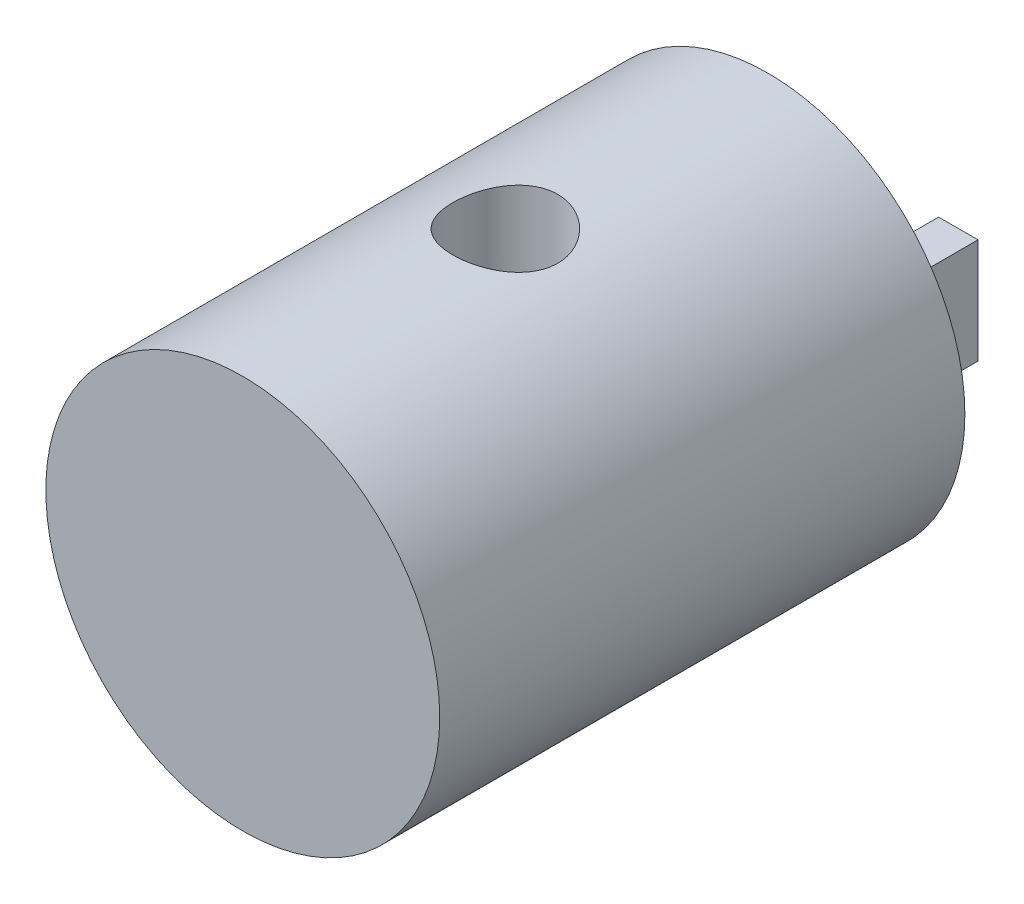
SolidWorks part; units mm, degrees
ref_plane "Alzado" through (0, 0, 0) normal (0, 0, 1) x (1, 0, 0)
ref_plane "Planta" through (0, 0, 0) normal (0, 1, 0) x (1, 0, 0)
ref_plane "Vista lateral" through (0, 0, 0) normal (1, 0, 0) x (0, 0, -1)
sketch "Croquis1" plane through (0, 0, 0) normal (0, 0, 1) x (1, 0, 0)
  circle A0 centre (0, 0) radius 7.5
  dimension "D1" = 15
extrude "Saliente-Extruir1" add sketch "Croquis1" along normal blind 20
sketch "Croquis2" plane through (0, 0, 20) normal (0, 0, 1) x (1, 0, 0)
  line L0 (-2.5, 2) -> (-2.5, -2)
  line L1 (-2.5, -2) -> (2.5, -2)
  line L2 (2.5, -2) -> (2.5, 2)
  line L3 (2.5, 2) -> (-2.5, 2)
  point P2 (0, 2)
  point P5 (2.5, 0)
  dimension "D1" = 5
  dimension "D2" = 4
extrude "Saliente-Extruir2" add sketch "Croquis2" along normal blind 4
sketch "Croquis4" plane through (0, 0, 0) normal (0, 0, -1) x (-1, 0, 0)
  line L0 (-4, 2) -> (-4, -2)
  line L1 (-4, -2) -> (4, -2)
  line L2 (4, -2) -> (4, 2)
  line L3 (4, 2) -> (-4, 2)
  point P5 (4, 0)
  point P8 (0, -2)
  dimension "D1" = 8
  dimension "D2" = 4
extrude "Saliente-Extruir4" add sketch "Croquis4" along normal blind 4
sketch "Croquis6" plane through (0, 2, 0) normal (0, 1, 0) x (1, 0, 0)
  line L0 (-2.5, 4) -> (-2.5, 0)
  line L1 (-2.5, 0) -> (2.5, 0)
  line L2 (2.5, 0) -> (2.5, 4)
  line L3 (2.5, 4) -> (-2.5, 4)
  line L4 (-1.25, -20) -> (-1.25, -24)
  line L5 (-1.25, -24) -> (1.25, -24)
  line L6 (1.25, -24) -> (1.25, -20)
  line L7 (1.25, -20) -> (-1.25, -20)
  line L10 (-4, 4) -> (4, 4) construction
  line L11 (2.5, -24) -> (-2.5, -24) construction
  point P12 (0, 4)
  point P13 (0, 4)
  point P14 (0, -24)
  point P15 (0, -24)
  dimension "D1" = 5
  dimension "D2" = 4
  dimension "D3" = 4
  dimension "D4" = 2.5
extrude "Cortar-Extruir1" cut sketch "Croquis6" against normal up to next
sketch "Croquis7" plane through (-4, 0, 0) normal (-1, 0, 0) x (0, 0, 1)
  line L0 (-4, -2) -> (-4, 2) construction
  line L1 (24, 2) -> (24, -2) construction
  circle A0 centre (-2.5, 0) radius 1
  circle A1 centre (22.5, 0) radius 1
  dimension "D3" = 2
  dimension "D4" = 2
  dimension "D1" = 1.5
  dimension "D2" = 1.5
extrude "Cortar-Extruir2" cut sketch "Croquis7" against normal blind 5
sketch "Croquis8" plane through (0, 2, 0) normal (0, 1, 0) x (1, 0, 0)
  line L0 (-7.5, -20) -> (7.5, -20) construction
  line L1 (7.5, 0) -> (-7.5, 0) construction
  circle A0 centre (0, -10) radius 2
  dimension "D1" = 4
  dimension "D2" = 10
  dimension "D3" = 10
extrude "Cortar-Extruir3" cut sketch "Croquis8" against normal up to next and the other way up to next
sketch "Croquis9" plane through (2.5, 0, 0) normal (1, 0, 0) x (0, 0, -1)
  line L1 (-24, 2) -> (-20, 2)
  line L2 (-24, 2) -> (-24, -2)
  line L3 (-24, -2) -> (-20, -2)
  line L4 (-20, 2) -> (-20, -2)
extrude "Cortar-Extruir4" cut sketch "Croquis9" against normal blind 5
